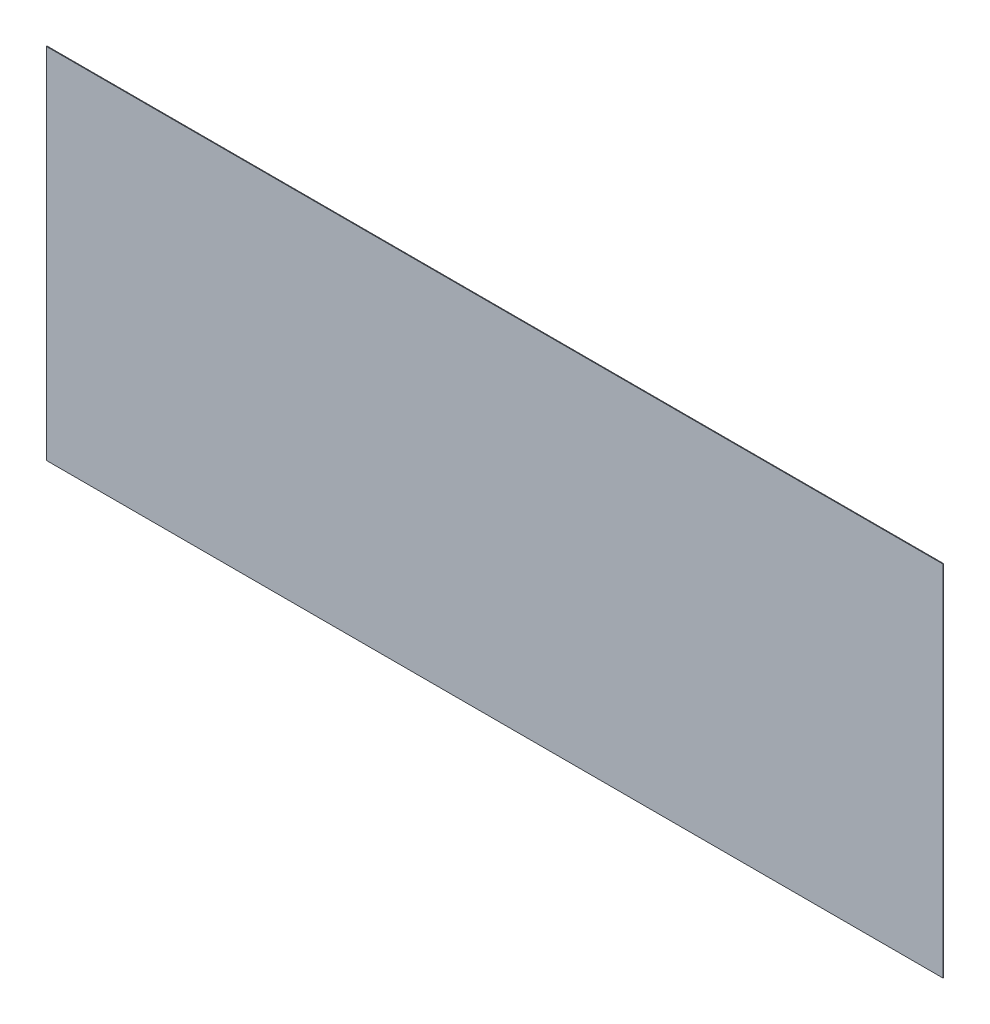
SolidWorks part; units mm, degrees
ref_plane "Front" through (0, 0, 0) normal (0, 0, 1) x (1, 0, 0)
ref_plane "Top" through (0, 0, 0) normal (0, 1, 0) x (1, 0, 0)
ref_plane "Right" through (0, 0, 0) normal (1, 0, 0) x (0, 0, -1)
sketch "Эскиз1" plane through (0, 0, 0) normal (0, 0, 1) x (1, 0, 0)
  line L1 (-625, 500) -> (625, 500)
  line L2 (-625, 500) -> (-625, 0)
  line L3 (-625, 0) -> (625, 0)
  line L4 (625, 500) -> (625, 0)
  dimension "D1" = 500
  dimension "D2" = 1250
extrude "Бобышка-Вытянуть1" add sketch "Эскиз1" along normal blind 1
